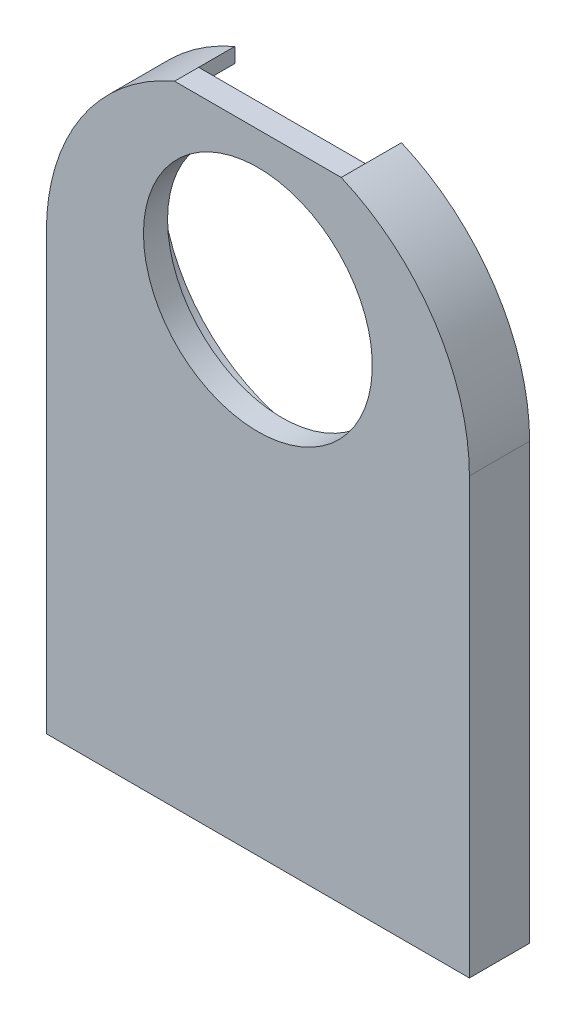
SolidWorks part; units mm, degrees
ref_plane "Front Plane" through (0, 0, 0) normal (0, 0, 1) x (1, 0, 0)
ref_plane "Top Plane" through (0, 0, 0) normal (0, 1, 0) x (1, 0, 0)
ref_plane "Right Plane" through (0, 0, 0) normal (1, 0, 0) x (0, 0, -1)
sketch "Sketch1" plane through (0, 0, 0) normal (0, 0, 1) x (1, 0, 0)
  line L0 (5.32, 14.0026) -> (5.32, 14.6195)
  line L1 (0, 0) -> (17.56, 0)
  line L2 (0, 0) -> (0, 6.55)
  line L3 (0, 6.55) -> (17.56, 6.55)
  line L4 (17.56, 0) -> (17.56, 6.55)
  line L6 (12.24, 14.0026) -> (12.24, 14.6195)
  arc A0 (5.32, 14.6195) -> (0, 6.55) centre (8.78, 6.55) ccw
  arc A1 (5.32, 14.0026) -> (12.24, 14.0026) centre (8.78, 8.5) ccw
  arc A2 (17.56, 6.55) -> (12.24, 14.6195) centre (8.78, 6.55) ccw
  dimension "D4" = 13
  dimension "D1" = 17.56
  dimension "D2" = 6.55
  dimension "D5" = 1.95
  dimension "D6" = 5.32
extrude "Boss-Extrude1" add sketch "Sketch1" along normal blind 1.5 contours A1 L3 L2 L1 L4 | A1 L0 A0 L3 | L3 A2 L6 A1
sketch "Sketch3" plane through (0, 0, 1.5) normal (0, 0, 1) x (1, 0, 0)
  line L5 (5.32, 14.0026) -> (5.32, 14.6195)
  line L6 (0, 6.55) -> (0, 0)
  line L7 (0, 0) -> (17.56, 0)
  line L8 (17.56, 0) -> (17.56, 6.55)
  line L9 (12.24, 14.6195) -> (12.24, 14.0026)
  line L10 (5.32, 14.0026) -> (5.32, 14.6195)
  line L11 (0, 6.55) -> (0, 0)
  line L12 (0, 0) -> (17.56, 0)
  line L13 (17.56, 0) -> (17.56, 6.55)
  line L14 (12.24, 14.6195) -> (12.24, 14.0026)
  line L15 (0, 0) -> (17.56, 0)
  line L16 (17.56, 6.55) -> (17.56, 0)
  line L17 (0, 0) -> (0, 6.55)
  line L18 (5.32, 14.6195) -> (12.24, 14.6195)
  arc A3 (5.32, 14.0026) -> (12.24, 14.0026) centre (8.78, 8.5) ccw
  arc A4 (5.32, 14.6195) -> (0, 6.55) centre (8.78, 6.55) ccw
  arc A5 (17.56, 6.55) -> (12.24, 14.6195) centre (8.78, 6.55) ccw
  arc A6 (5.32, 14.0026) -> (12.24, 14.0026) centre (8.78, 8.5) ccw
  arc A7 (5.32, 14.6195) -> (0, 6.55) centre (8.78, 6.55) ccw
  arc A8 (17.56, 6.55) -> (12.24, 14.6195) centre (8.78, 6.55) ccw
  arc A9 (17.56, 6.55) -> (12.24, 14.6195) centre (8.78, 6.55) ccw
  arc A10 (0, 6.55) -> (5.32, 14.6195) centre (8.78, 6.55) cw
  arc M9 (12.24, 14.0026) -> (5.32, 14.0026) centre (8.78, 8.5) cw
  line M10 (5.32, 14.0026) -> (5.32, 14.6195)
  arc M11 (5.32, 14.6195) -> (0, 6.55) centre (8.78, 6.55) ccw
  line M12 (0, 6.55) -> (0, 0)
  line M13 (0, 0) -> (17.56, 0)
  line M14 (17.56, 0) -> (17.56, 6.55)
  arc M15 (17.56, 6.55) -> (12.24, 14.6195) centre (8.78, 6.55) ccw
  line M16 (12.24, 14.6195) -> (12.24, 14.0026)
  dimension "D1" = 0
extrude "Boss-Extrude2" add sketch "Sketch3" along normal blind 1 contours M16 M9 M10 M11 M12 M13 M14 M15 | L18 M10 M9 M16
sketch "Sketch4" plane through (0, 0, 1.5) normal (0, 0, -1) x (-1, 0, 0)
  circle A0 centre (-8.78, 8.5) radius 4.75
  dimension "D1" = 9.5
extrude "Cut-Extrude1" cut sketch "Sketch4" against normal through all
sketch "Sketch5" plane through (0, 0, 0) normal (0, -1, 0) x (1, 0, 0)
  line L1 (0, 2.5) -> (17.56, 2.5)
  line L2 (0, 2.5) -> (0, 0)
  line L3 (0, 0) -> (17.56, 0)
  line L4 (17.56, 2.5) -> (17.56, 0)
extrude "Boss-Extrude3" add sketch "Sketch5" along normal blind 0.15
sketch "Sketch6" plane through (0, -0.15, 0) normal (0, -1, 0) x (1, 0, 0)
  line L4 (0, 2.5) -> (0, 0)
  line L5 (0, 0) -> (17.56, 0)
  line L6 (17.56, 0) -> (17.56, 2.5)
  line L7 (17.56, 2.5) -> (0, 2.5)
  line L8 (0, 2.5) -> (0, 0)
  line L9 (0, 0) -> (17.56, 0)
  line L10 (17.56, 0) -> (17.56, 2.5)
  line L11 (17.56, 2.5) -> (0, 2.5)
  dimension "D1" = 0
extrude "Boss-Extrude4" add sketch "Sketch6" along normal blind 11.35
